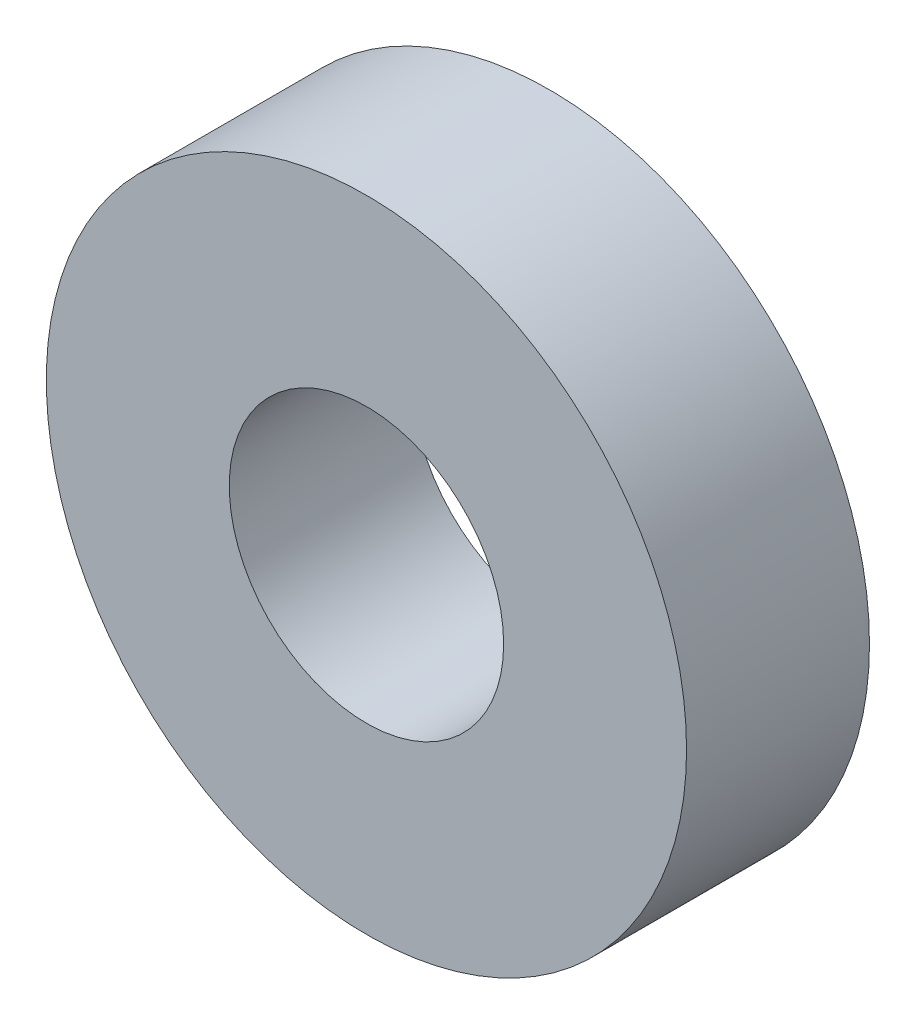
SolidWorks part; units mm, degrees
ref_plane "Front Plane" through (0, 0, 0) normal (0, 0, 1) x (1, 0, 0)
ref_plane "Top Plane" through (0, 0, 0) normal (0, 1, 0) x (1, 0, 0)
ref_plane "Right Plane" through (0, 0, 0) normal (1, 0, 0) x (0, 0, -1)
sketch "Sketch1" plane through (0, 0, 0) normal (0, 0, 1) x (1, 0, 0)
  circle A0 centre (0, 0) radius 1.905
  circle A1 centre (0, 0) radius 4.445
  dimension "D1" = 3.81
  dimension "D2" = 2.54
extrude "Boss-Extrude1" add sketch "Sketch1" along normal blind 2.54
